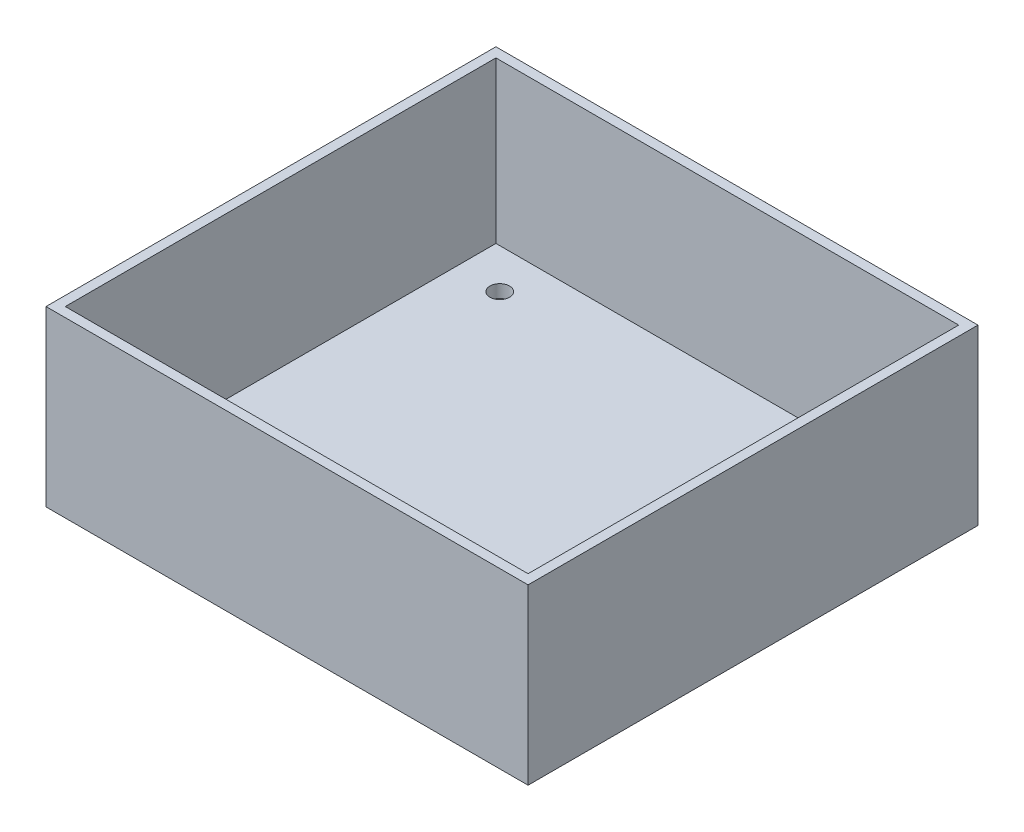
SolidWorks part; units mm, degrees
material "PE Alta densidad"
ref_plane "Alzado" through (0, 0, 0) normal (0, 0, 1) x (1, 0, 0)
ref_plane "Planta" through (0, 0, 0) normal (0, 1, 0) x (1, 0, 0)
ref_plane "Vista lateral" through (0, 0, 0) normal (1, 0, 0) x (0, 0, -1)
sketch "Croquis1" plane through (0, 0, 0) normal (0, 1, 0) x (1, 0, 0)
  line L0 (0, 30.8063) -> (0, -22.2144) construction
  line L5 (-11.0734, 0) -> (15.5778, 0) construction
  line L6 (-37.5, 35) -> (37.5, 35)
  line L7 (-37.5, 35) -> (-37.5, -35)
  line L8 (-37.5, -35) -> (37.5, -35)
  line L9 (37.5, 35) -> (37.5, -35)
  dimension "D1" = 75
  dimension "D2" = 70
extrude "Saliente-Extruir1" add sketch "Croquis1" along normal blind 2
sketch "Croquis2" plane through (0, 2, 0) normal (0, 1, 0) x (1, 0, 0)
  line L1 (-37.5, 35) -> (37.5, 35)
  line L2 (-37.5, 35) -> (-37.5, -35)
  line L3 (-37.5, -35) -> (37.5, -35)
  line L4 (37.5, 35) -> (37.5, -35)
  line L5 (-36, 33.5) -> (36, 33.5)
  line L6 (-36, 33.5) -> (-36, -33.5)
  line L7 (-36, -33.5) -> (36, -33.5)
  line L8 (36, 33.5) -> (36, -33.5)
  point P4 (-32.7567, 36.0437)
  dimension "D1" = 1.5
  dimension "D2" = 1.5
  dimension "D3" = 1.5
  dimension "D4" = 1.5
extrude "Saliente-Extruir2" add sketch "Croquis2" along normal blind 25
sketch "Croquis3" plane through (0, 2, 0) normal (0, 1, 0) x (1, 0, 0)
  line L0 (0, 18.7945) -> (0, -12.7364) construction
  line L1 (-12.8564, 0) -> (15.7655, 0) construction
  circle A5 centre (-29.21, 27.305) radius 1.525
  circle A6 centre (-29.21, -27.305) radius 1.525
  circle A7 centre (29.21, 27.305) radius 1.525
  circle A8 centre (29.21, -27.305) radius 1.525
  dimension "D1" = 3.05
  dimension "D2" = 54.61
  dimension "D3" = 58.42
  dimension "D4" = 54.61
  dimension "D5" = 58.42
extrude "Cortar-Extruir1" cut sketch "Croquis3" against normal blind 10
